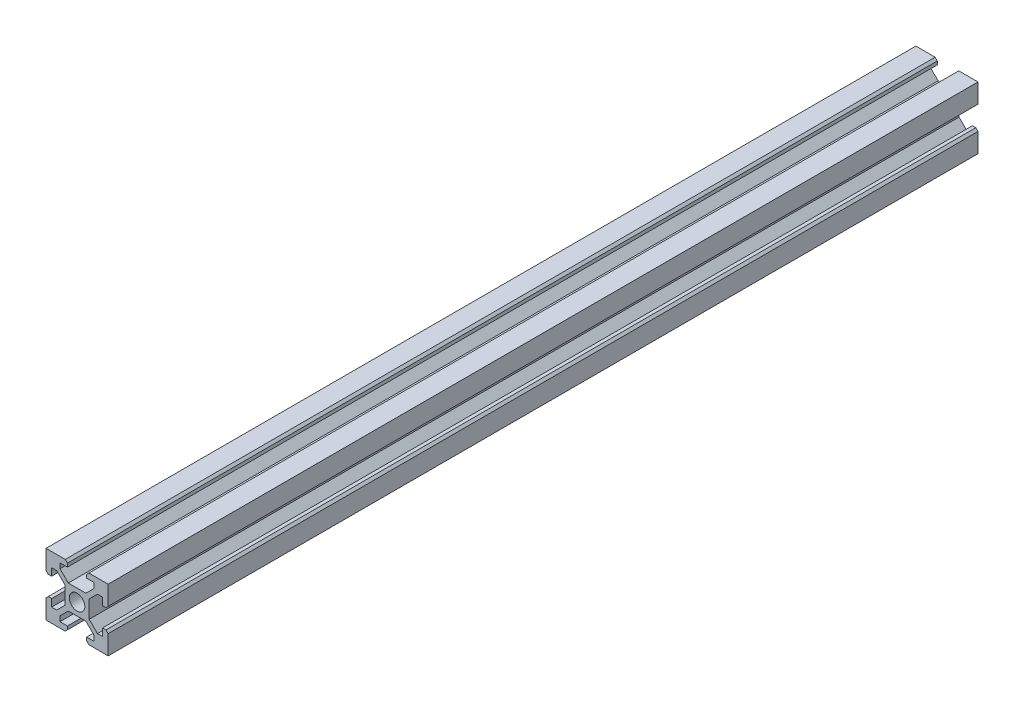
SolidWorks part; units mm, degrees
material "1060 Alloy"
ref_plane "Front Plane" through (0, 0, 0) normal (0, 0, 1) x (1, 0, 0)
ref_plane "Top Plane" through (0, 0, 0) normal (0, 1, 0) x (1, 0, 0)
ref_plane "Right Plane" through (0, 0, 0) normal (1, 0, 0) x (0, 0, -1)
sketch "Sketch1" plane through (0, 0, 0) normal (0, 0, 1) x (1, 0, 0)
  line L0 (3.9, -2.8393) -> (6.5607, -5.5)
  line L1 (-10, 10) -> (10, 10) construction
  line L2 (-10, 10) -> (-10, -10) construction
  line L3 (-10, -10) -> (10, -10) construction
  line L4 (10, 10) -> (10, -10) construction
  line L5 (-10, 10) -> (10, -10) construction
  line L6 (-10, -10) -> (10, 10) construction
  line L7 (-3.9, -3.9) -> (3.9, -3.9) construction
  line L8 (-3.9, -3.9) -> (-3.9, 3.9) construction
  line L9 (-3.9, 3.9) -> (3.9, 3.9) construction
  line L10 (3.9, -3.9) -> (3.9, 3.9) construction
  line L11 (-3.9, -3.9) -> (3.9, 3.9) construction
  line L12 (-3.9, 3.9) -> (3.9, -3.9) construction
  line L13 (-10, 10) -> (-5.5, 10) construction
  line L14 (-10, 10) -> (-10, 5.5) construction
  line L15 (-10, 5.5) -> (-5.5, 5.5) construction
  line L16 (-5.5, 10) -> (-5.5, 5.5) construction
  line L17 (10, 10) -> (5.5, 10) construction
  line L18 (10, 10) -> (10, 5.5) construction
  line L19 (10, 5.5) -> (5.5, 5.5) construction
  line L20 (5.5, 10) -> (5.5, 5.5) construction
  line L21 (-10, -10) -> (-5.5, -10) construction
  line L22 (-10, -10) -> (-10, -5.5) construction
  line L23 (-10, -5.5) -> (-5.5, -5.5) construction
  line L24 (-5.5, -10) -> (-5.5, -5.5) construction
  line L25 (10, -10) -> (5.5, -10) construction
  line L26 (10, -10) -> (10, -5.5) construction
  line L27 (10, -5.5) -> (5.5, -5.5) construction
  line L28 (5.5, -10) -> (5.5, -5.5) construction
  line L29 (2.8393, -3.9) -> (5.5, -6.5607)
  line L30 (-5.5, 6.5607) -> (-2.8393, 3.9)
  line L31 (-6.5607, 5.5) -> (-3.9, 2.8393)
  line L32 (5.5, 6.5607) -> (2.8393, 3.9)
  line L33 (6.5607, 5.5) -> (3.9, 2.8393)
  line L34 (-6.5607, -5.5) -> (-3.9, -2.8393)
  line L35 (-5.5, -6.5607) -> (-2.8393, -3.9)
  line L36 (-2.8393, 3.9) -> (2.8393, 3.9)
  line L37 (-3.9, 2.8393) -> (-3.9, -2.8393)
  line L38 (-2.8393, -3.9) -> (2.8393, -3.9)
  line L39 (3.9, -2.8393) -> (3.9, 2.8393)
  line L40 (5.5, 6.5607) -> (5.5, 8.2007)
  line L41 (5.5, 8.2007) -> (3.1, 8.2007)
  line L42 (3.1, 8.2007) -> (3.1, 9.3)
  line L43 (3.1, 9.3) -> (3.8, 10)
  line L44 (3.8, 10) -> (10, 10)
  line L45 (10, 10) -> (10, 3.8)
  line L46 (10, 3.8) -> (9.3, 3.1)
  line L47 (9.3, 3.1) -> (8.2007, 3.1)
  line L48 (8.2007, 3.1) -> (8.2007, 5.5)
  line L49 (8.2007, 5.5) -> (6.5607, 5.5)
  line L50 (3.1, -8.2007) -> (5.5, -8.2007)
  line L51 (3.1, -9.3) -> (3.1, -8.2007)
  line L52 (3.8, -10) -> (3.1, -9.3)
  line L53 (10, -10) -> (3.8, -10)
  line L54 (10, -3.8) -> (10, -10)
  line L55 (9.3, -3.1) -> (10, -3.8)
  line L56 (8.2007, -3.1) -> (9.3, -3.1)
  line L57 (8.2007, -5.5) -> (8.2007, -3.1)
  line L58 (6.5607, -5.5) -> (8.2007, -5.5)
  line L59 (5.5, -8.2007) -> (5.5, -6.5607)
  line L60 (-8.2007, -3.1) -> (-8.2007, -5.5)
  line L61 (-9.3, -3.1) -> (-8.2007, -3.1)
  line L62 (-10, -3.8) -> (-9.3, -3.1)
  line L63 (-10, -10) -> (-10, -3.8)
  line L64 (-3.8, -10) -> (-10, -10)
  line L65 (-3.1, -9.3) -> (-3.8, -10)
  line L66 (-3.1, -8.2007) -> (-3.1, -9.3)
  line L67 (-5.5, -8.2007) -> (-3.1, -8.2007)
  line L68 (-5.5, -6.5607) -> (-5.5, -8.2007)
  line L69 (-8.2007, -5.5) -> (-6.5607, -5.5)
  line L70 (-3.1, 8.2007) -> (-5.5, 8.2007)
  line L71 (-3.1, 9.3) -> (-3.1, 8.2007)
  line L72 (-3.8, 10) -> (-3.1, 9.3)
  line L73 (-10, 10) -> (-3.8, 10)
  line L74 (-10, 3.8) -> (-10, 10)
  line L75 (-9.3, 3.1) -> (-10, 3.8)
  line L76 (-8.2007, 3.1) -> (-9.3, 3.1)
  line L77 (-8.2007, 5.5) -> (-8.2007, 3.1)
  line L78 (-6.5607, 5.5) -> (-8.2007, 5.5)
  line L79 (-5.5, 8.2007) -> (-5.5, 6.5607)
  circle A0 centre (0, 0) radius 2.5
  point P83 (0, 0)
  dimension "D1" = 5
  dimension "D2" = 20
  dimension "D3" = 7.8
  dimension "D4" = 4.5
  dimension "D5" = 1.5
  dimension "D6" = 0.75
  dimension "D7" = 1.5
  dimension "D8" = 0.75
  dimension "D9" = 1.5
  dimension "D10" = 0.75
  dimension "D11" = 1.5
  dimension "D12" = 0.75
  dimension "D13" = 1.64
  dimension "D14" = 45
  dimension "D15" = 3.1
  dimension "D16" = 6.2
  dimension "D17" = 6.2
  dimension "D18" = 3.1
  dimension "D19" = 4
extrude "Boss-Extrude1" add sketch "Sketch1" along normal mid plane 280 contours L79 L70 L71 L72 L73 L74 L75 L76 L77 L78 L31 L37 L34 L69 L60 L61 L62 L63 L64 L65 L66 L67 L68 L35 L38 L29 L59 L50 L51 L52 L53 L54 L55 L56 L57 L58 L0 L39 L33 L49 L48 L47 L46 L45 L44 L43 L42 L41 L40 L32 L36
